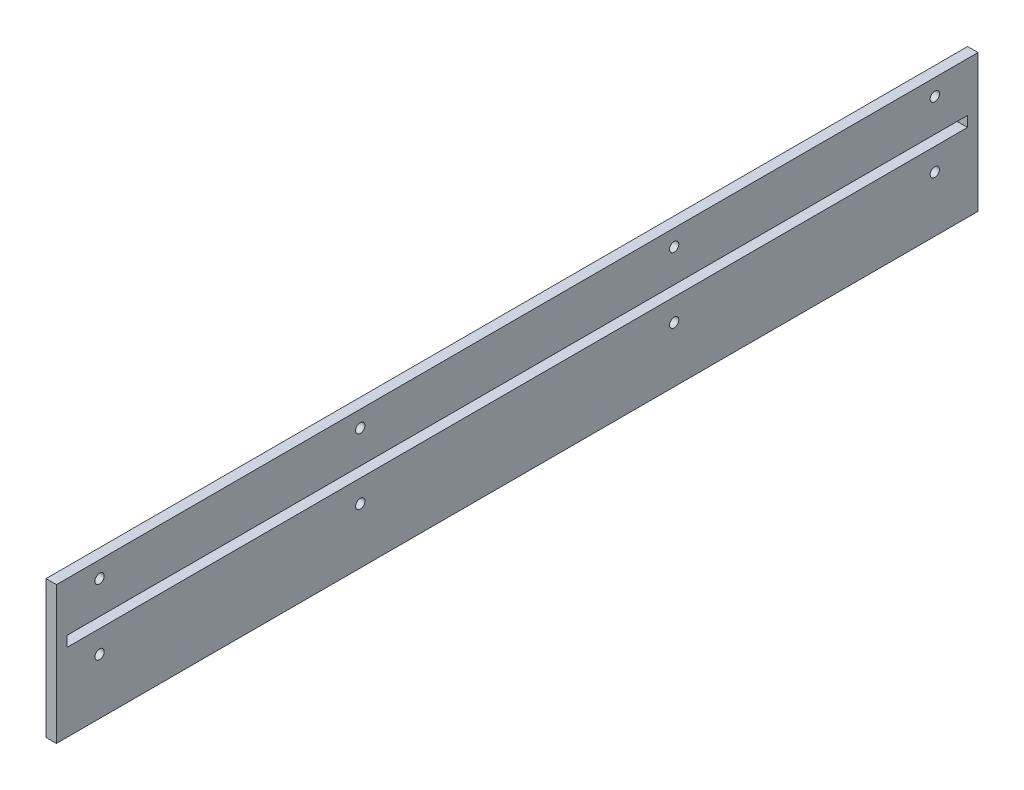
SolidWorks part; units mm, degrees
ref_plane "Front Plane" through (0, 0, 0) normal (0, 0, 1) x (1, 0, 0)
ref_plane "Top Plane" through (0, 0, 0) normal (0, 1, 0) x (1, 0, 0)
ref_plane "Right Plane" through (0, 0, 0) normal (1, 0, 0) x (0, 0, -1)
sketch "Sketch1" plane through (0, 0, 0) normal (1, 0, 0) x (0, 0, -1)
  line L1 (-140.68, 15) -> (140.68, 15)
  line L2 (-140.68, 15) -> (-140.68, -15)
  line L3 (-140.68, -15) -> (140.68, -15)
  line L4 (140.68, 15) -> (140.68, -15)
  line L5 (-140.68, 15) -> (140.68, -15) construction
  line L6 (-140.68, -15) -> (140.68, 15) construction
  point P0 (0, 0)
  dimension "D1" = 30
  dimension "D2" = 281.36
extrude "Boss-Extrude1" add sketch "Sketch1" along normal blind 3.18
sketch "Sketch2" plane through (0, 0, 0) normal (-1, 0, 0) x (0, 0, 1)
  line L0 (-140.68, 0) -> (0, 0) construction
  line L1 (-140.68, -15) -> (-140.68, 15) construction
  line L2 (0, 0) -> (0, 15) construction
  line L3 (-140.68, 15) -> (140.68, 15) construction
  line L4 (0, 7.5) -> (-140.68, 7.5) construction
  line L5 (-127.5, 10) -> (-127.5, 5) construction
  line L6 (-127.5, 10) -> (-47.91, 10) construction
  circle A0 centre (-127.5, 10) radius 1.425
  circle A2 centre (-47.91, 10) radius 1.425
  point P14 (-127.5, 7.5)
  dimension "D1" = 2.85
  dimension "D2" = 5
  dimension "D5" = 2.85
  dimension "D3" = 13.18
  dimension "D4" = 79.59
extrude "Cut-Extrude1" cut sketch "Sketch2" against normal up to next
mirror "Mirror1" about plane through (0, 0, 0) normal (0, 1, 0) of "Cut-Extrude1"
mirror "Mirror2" about plane through (0, 0, 0) normal (0, 0, 1) of "Mirror1", "Cut-Extrude1"
sketch "Sketch3" plane through (3.18, 0, 0) normal (1, 0, 0) x (0, 0, -1)
  line L1 (-137.5, -3.21) -> (137.5, -3.21)
  line L2 (-137.5, -3.21) -> (-137.5, -0.02)
  line L3 (-137.5, -0.02) -> (137.5, -0.02)
  line L4 (137.5, -3.21) -> (137.5, -0.02)
  line L6 (140.68, 15) -> (-140.68, 15) construction
  line L7 (-140.68, -15) -> (140.68, -15) construction
  point P6 (0, -3.21)
  point P9 (0, -15)
  dimension "D1" = 3.19
  dimension "D2" = 275
  dimension "D3" = 15.02
extrude "Cut-Extrude2" cut sketch "Sketch3" against normal blind 3.18
sketch "Sketch4" plane through (0, -15, 0) normal (0, -1, 0) x (1, 0, 0)
  line L1 (3.18, -140.68) -> (0, -140.68)
  line L2 (3.18, -140.68) -> (3.18, 140.68)
  line L3 (3.18, 140.68) -> (0, 140.68)
  line L4 (0, -140.68) -> (0, 140.68)
extrude "Boss-Extrude2" add sketch "Sketch4" along normal blind 12
